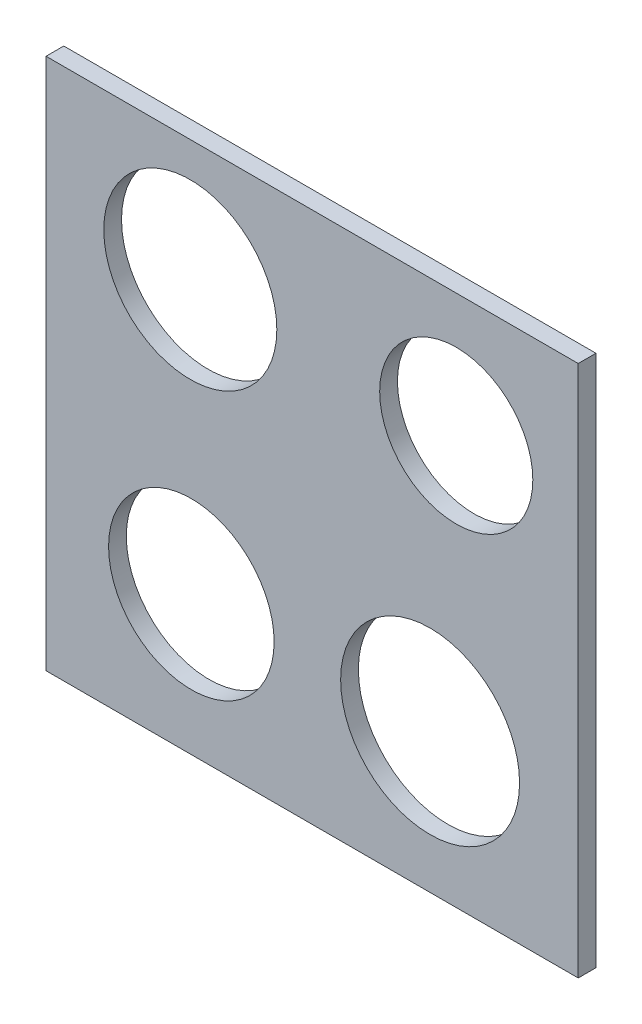
SolidWorks part; units mm, degrees
ref_plane "Front Plane" through (0, 0, 0) normal (0, 0, 1) x (1, 0, 0)
ref_plane "Top Plane" through (0, 0, 0) normal (0, 1, 0) x (1, 0, 0)
ref_plane "Right Plane" through (0, 0, 0) normal (1, 0, 0) x (0, 0, -1)
sketch "Sketch1" plane through (0, 0, 0) normal (0, 0, 1) x (1, 0, 0)
  line L1 (-15, 15) -> (15, 15)
  line L2 (-15, 15) -> (-15, -15)
  line L3 (-15, -15) -> (15, -15)
  line L4 (15, 15) -> (15, -15)
  line L5 (-15, 15) -> (15, -15) construction
  line L6 (-15, -15) -> (15, 15) construction
  point P0 (0, 0)
  dimension "D1" = 30
  dimension "D2" = 30
extrude "Boss-Extrude1" add sketch "Sketch1" along normal blind 1
sketch "Sketch2" plane through (0, 0, 0) normal (0, 0, -1) x (-1, 0, 0)
  circle A0 centre (-8.1243, 8.039) radius 4.3162
  point P2 (-8.8602, 8.1981)
  point P3 (-8.1243, 8.039)
extrude "Cut-Extrude1" cut sketch "Sketch2" against normal blind 3
sketch "Sketch3" plane through (0, 0, 0) normal (0, 0, -1) x (-1, 0, 0)
  circle A0 centre (-6.6503, -7.1314) radius 5.0431
  point P2 (-6.6503, -7.1314)
extrude "Cut-Extrude2" cut sketch "Sketch3" against normal blind 3
sketch "Sketch4" plane through (0, 0, 0) normal (0, 0, -1) x (-1, 0, 0)
  circle A0 centre (6.8675, 8.162) radius 4.8774
  point P2 (6.8675, 8.162)
extrude "Cut-Extrude3" cut sketch "Sketch4" against normal blind 3
sketch "Sketch5" plane through (0, 0, 0) normal (0, 0, -1) x (-1, 0, 0)
  circle A0 centre (6.8087, -7.1653) radius 4.6664
  point P2 (6.8087, -7.1653)
extrude "Cut-Extrude4" cut sketch "Sketch5" against normal blind 3
